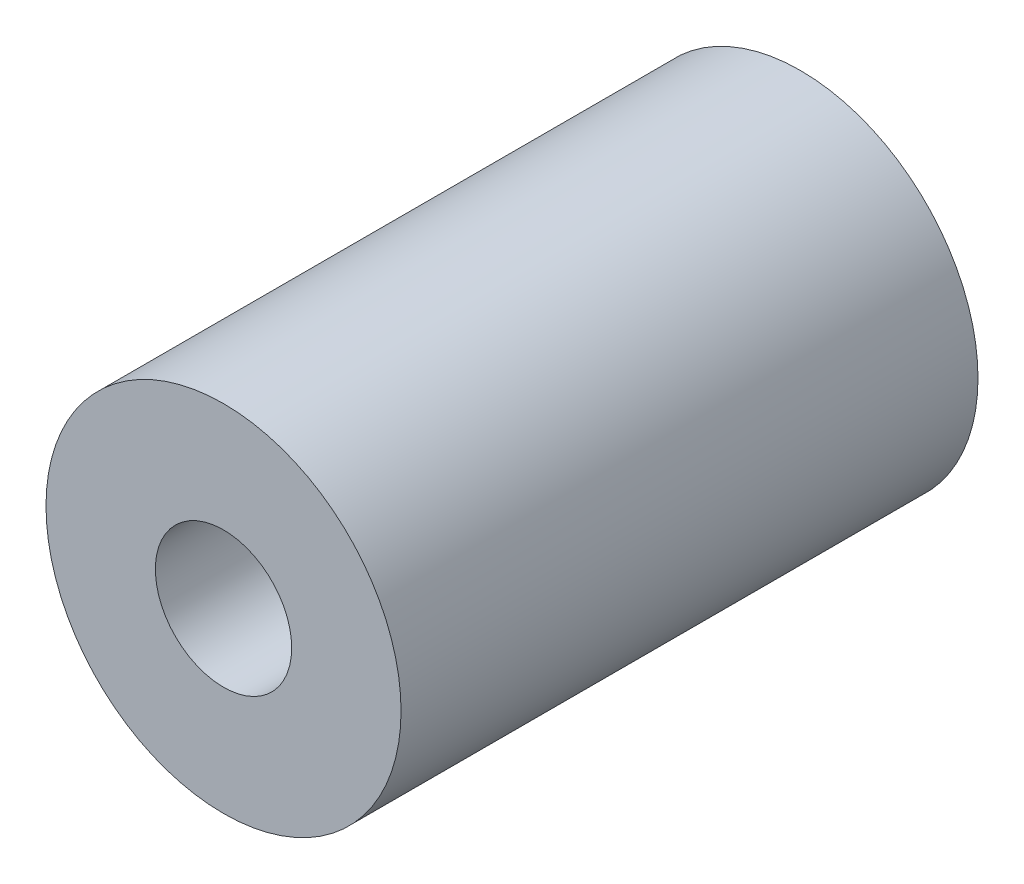
SolidWorks part; units mm, degrees
material "Nylon 101"
ref_plane "Front Plane" through (0, 0, 0) normal (0, 0, 1) x (1, 0, 0)
ref_plane "Top Plane" through (0, 0, 0) normal (0, 1, 0) x (1, 0, 0)
ref_plane "Right Plane" through (0, 0, 0) normal (1, 0, 0) x (0, 0, -1)
sketch "Sketch1" plane through (0, 0, 0) normal (0, 0, 1) x (1, 0, 0)
  circle A0 centre (0, 0) radius 6.35
  circle A1 centre (0, 0) radius 2.4384
  dimension "OD" = 12.7
  dimension "ID" = 4.8768
extrude "Extrude1" add sketch "Sketch1" along normal mid plane 20.6375
sketch "Sketch2" plane through (0, 0, 0) normal (1, 0, 0) x (0, 0, -1)
  line L0 (-10.3187, -2.4384) -> (10.3187, -2.4384) construction
  line L3 (10.3187, 2.4384) -> (-10.3187, 2.4384) construction
  line L5 (-10.3187, -2.4384) -> (10.3187, -2.4384)
  line L6 (10.3187, 2.4384) -> (-10.3187, 2.4384)
sketch "Sketch4" plane through (0, 0, 10.3187) normal (0, 0, 1) x (1, 0, 0)
  line L0 (0, 0) -> (-1.7242, 1.7242)
  line L1 (0, -6.985) -> (0, 6.985) construction
  circle A0 centre (0, 0) radius 2.4384 construction
  dimension "D1" = 45
